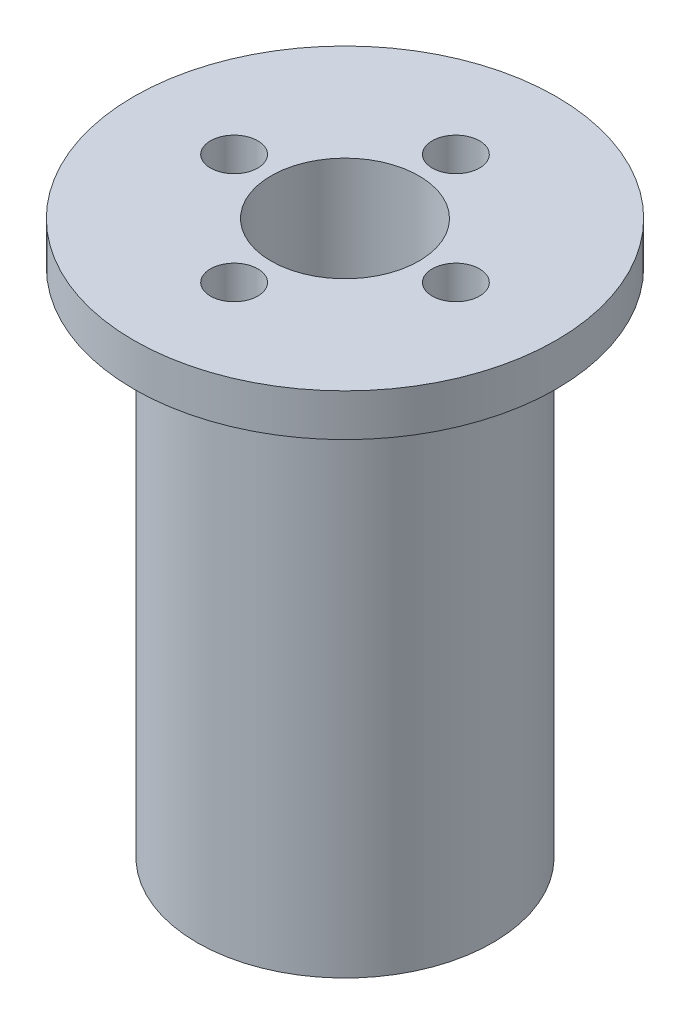
SolidWorks part; units mm, degrees
ref_plane "Ebene vorne" through (0, 0, 0) normal (0, 0, 1) x (1, 0, 0)
ref_plane "Ebene oben" through (0, 0, 0) normal (0, 1, 0) x (1, 0, 0)
ref_plane "Ebene rechts" through (0, 0, 0) normal (1, 0, 0) x (0, 0, -1)
sketch "Skizze4" plane through (0, 0, 0) normal (1, 0, 0) x (0, 0, -1)
  line L0 (8.75, 0) -> (25, 0)
  line L1 (25, 0) -> (25, -5)
  line L2 (25, -5) -> (19.5, -5)
  line L3 (19.5, -5) -> (19.5, -6)
  line L4 (19.5, -6) -> (17.5, -6)
  line L5 (17.5, -6) -> (17.5, -65.5)
  line L6 (17.5, -65.5) -> (8.75, -65.5)
  line L7 (8.75, -65.5) -> (8.75, 0)
  line L8 (0, 0) -> (0, -40.4777) construction
  dimension "D1" = 8.75
  dimension "D2" = 25
  dimension "D3" = 19.5
  dimension "D4" = 17.5
  dimension "D5" = 59.5
  dimension "D6" = 5
  dimension "D7" = 1
revolve "Rotation1" add sketch "Skizze4" angle 360 about L8
sketch "Skizze5" plane through (0, 0, 0) normal (0, 1, 0) x (1, 0, 0)
  line L0 (0, 8.75) -> (0, 17.5) construction
  circle A0 centre (0, 0) radius 17.5
  circle A1 centre (0, 0) radius 8.75 construction
  circle A2 centre (0, 13.125) radius 2.8
  circle A3 centre (13.125, 0) radius 2.8
  circle A4 centre (0, -13.125) radius 2.8
  circle A5 centre (-13.125, 0) radius 2.8
  point P18 (0, 0)
  dimension "D1" = 35
  dimension "D2" = 5.6
  dimension "D3" = 4
extrude "Schnitt-Linear austragen1" cut sketch "Skizze5" against normal blind 15 contours A2 | A3 | A5 | A4
sketch "Skizze7" plane through (0, -65.5, 0) normal (0, -1, 0) x (1, 0, 0)
  line L0 (0, 8.75) -> (0, 17.5) construction
  circle A0 centre (0, 0) radius 8.75
  circle A1 centre (0, 0) radius 17.5
  circle A2 centre (0, 13.125) radius 2.8
  circle A3 centre (13.125, 0) radius 2.8
  circle A4 centre (0, -13.125) radius 2.8
  circle A5 centre (-13.125, 0) radius 2.8
  point P17 (0, 0)
  dimension "D1" = 5.6
  dimension "D2" = 4
extrude "Schnitt-Linear austragen2" cut sketch "Skizze7" against normal blind 15 contours A3 | A4 | A5 | L0 A2 | A2 L0
